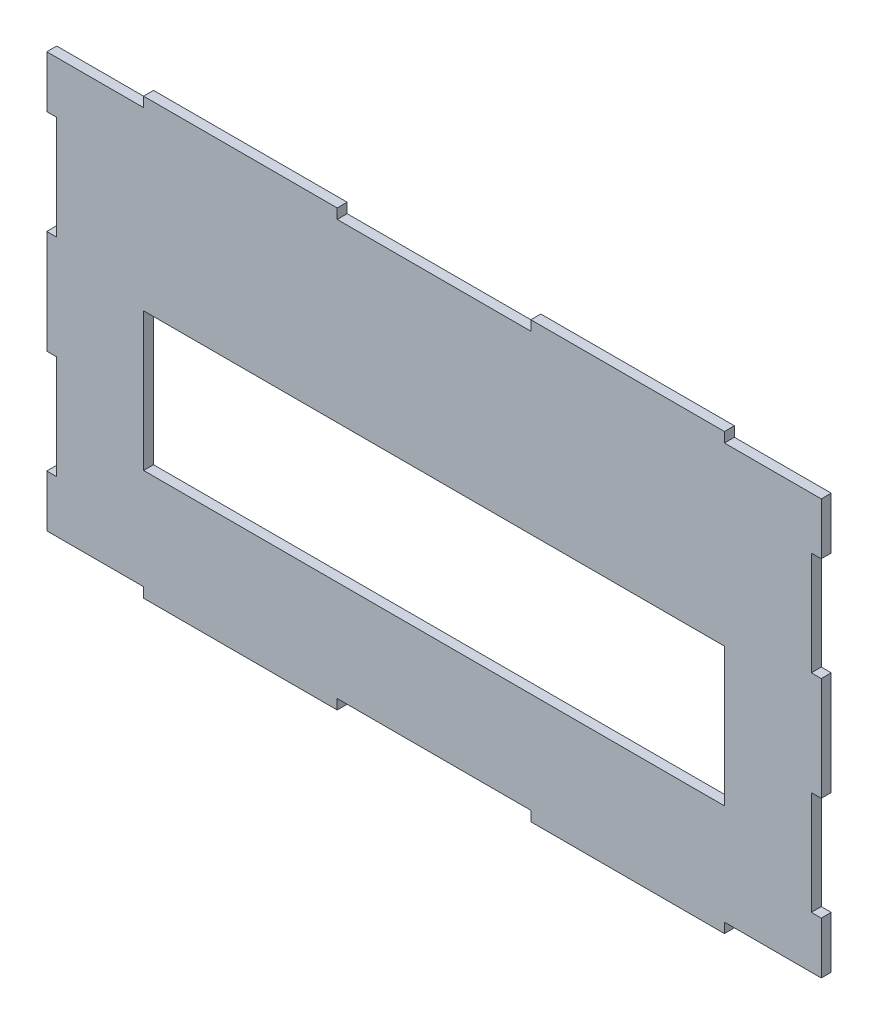
SolidWorks part; units mm, degrees
ref_plane "前视基准面" through (0, 0, 0) normal (0, 0, 1) x (1, 0, 0)
ref_plane "上视基准面" through (0, 0, 0) normal (0, 1, 0) x (1, 0, 0)
ref_plane "右视基准面" through (0, 0, 0) normal (1, 0, 0) x (0, 0, -1)
sketch "草图1" plane through (0, 0, 0) normal (0, 0, 1) x (1, 0, 0)
  line L5 (140, -75) -> (105, -75)
  line L6 (105, -75) -> (105, -78.6)
  line L7 (-140, 75) -> (-105, 75)
  line L8 (35, 75) -> (35, 78.6)
  line L9 (-105, 75) -> (-105, 78.6)
  line L10 (-105, 78.6) -> (-35, 78.6)
  line L11 (-35, 75) -> (-35, 78.6)
  line L12 (35, 75) -> (-35, 75)
  line L13 (105, 78.6) -> (35, 78.6)
  line L14 (105, 75) -> (105, 78.6)
  line L15 (140, 75) -> (105, 75)
  line L16 (105, -78.6) -> (35, -78.6)
  line L17 (35, -75) -> (-35, -75)
  line L18 (-35, -75) -> (-35, -78.6)
  line L19 (-105, -78.6) -> (-35, -78.6)
  line L20 (-105, -75) -> (-105, -78.6)
  line L21 (35, -75) -> (35, -78.6)
  line L22 (-140, -75) -> (-105, -75)
  line L23 (-140, 75) -> (-140, 56.25)
  line L24 (-140, -18.75) -> (-136.4, -18.75)
  line L25 (-140, 56.25) -> (-136.4, 56.25)
  line L26 (-136.4, 56.25) -> (-136.4, 18.75)
  line L27 (-140, 18.75) -> (-136.4, 18.75)
  line L28 (-140, 18.75) -> (-140, -18.75)
  line L29 (-136.4, -56.25) -> (-136.4, -18.75)
  line L30 (-140, -56.25) -> (-136.4, -56.25)
  line L31 (-140, -75) -> (-140, -56.25)
  line L32 (140, -75) -> (140, -56.25)
  line L33 (140, -56.25) -> (136.4, -56.25)
  line L34 (136.4, -56.25) -> (136.4, -18.75)
  line L35 (140, 18.75) -> (140, -18.75)
  line L36 (140, 18.75) -> (136.4, 18.75)
  line L37 (136.4, 56.25) -> (136.4, 18.75)
  line L38 (140, 56.25) -> (136.4, 56.25)
  line L39 (140, -18.75) -> (136.4, -18.75)
  line L40 (140, 75) -> (140, 56.25)
  point P0 (0, 0)
  point P14 (-70, 78.6)
  point P17 (70, 78.6)
  point P26 (70, -78.6)
  point P27 (-70, -78.6)
  point P34 (-136.4, 37.5)
  point P37 (-136.4, -37.5)
  point P46 (136.4, -37.5)
  point P47 (136.4, 37.5)
  dimension "D1" = 280
  dimension "D2" = 150
extrude "凸台-拉伸1" add sketch "草图1" along normal blind 3.6
sketch "草图2" plane through (0, 0, 3.6) normal (0, 0, 1) x (1, 0, 0)
  line L0 (-105, -78.6) -> (-35, -78.6) construction
  line L1 (-105, 11.4) -> (105, 11.4)
  line L2 (-105, 11.4) -> (-105, -38.6)
  line L3 (-105, -38.6) -> (105, -38.6)
  line L4 (105, 11.4) -> (105, -38.6)
  dimension "D1" = 50
  dimension "D2" = 210
  dimension "D3" = 40
  dimension "D4" = 105
extrude "切除-拉伸1" cut sketch "草图2" against normal blind 10
